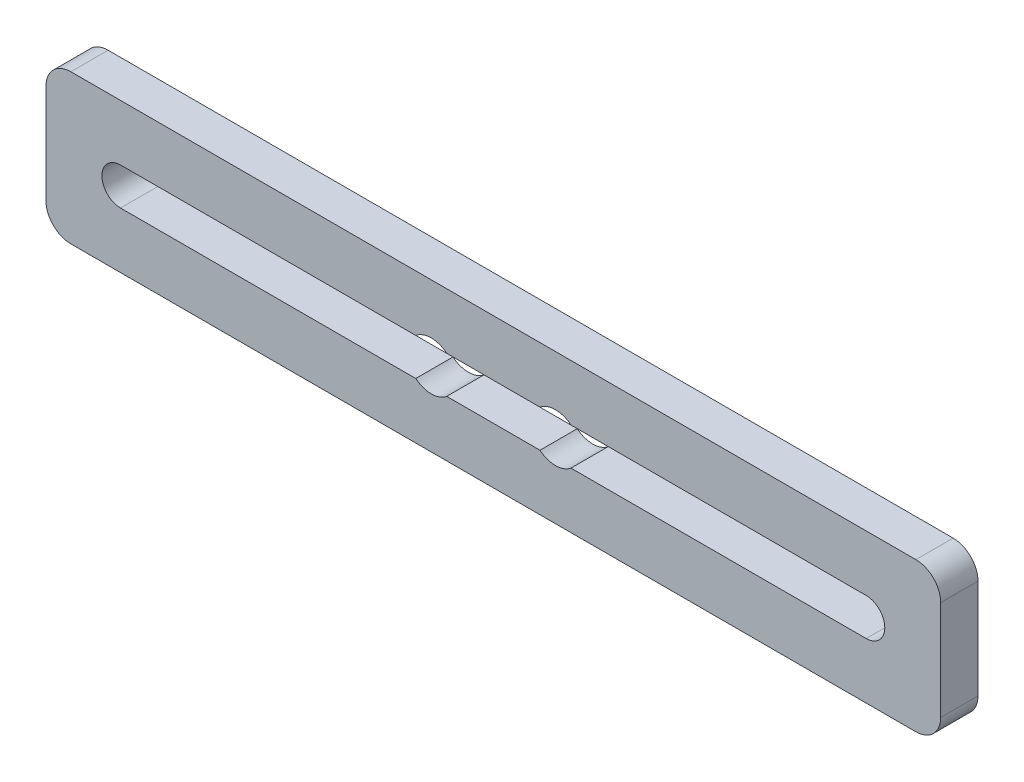
SolidWorks part; units mm, degrees
material "Thornel Mat VMA"
ref_plane "前视基准面" through (0, 0, 0) normal (0, 0, 1) x (1, 0, 0)
ref_plane "上视基准面" through (0, 0, 0) normal (0, 1, 0) x (1, 0, 0)
ref_plane "右视基准面" through (0, 0, 0) normal (1, 0, 0) x (0, 0, -1)
other "Configuration Table"
sketch "草图1" plane through (0, 0, 0) normal (0, 0, 1) x (1, 0, 0)
  line L1 (0, 0) -> (72, 0)
  line L2 (0, 0) -> (0, -12)
  line L3 (0, -12) -> (72, -12)
  line L4 (72, 0) -> (72, -12)
  dimension "D1" = 72
  dimension "D2" = 12
extrude "凸台-拉伸1" add sketch "草图1" along normal blind 3
sketch "草图2" plane through (0, 0, 3) normal (0, 0, 1) x (1, 0, 0)
  line L0 (0, -6) -> (72, -6) construction
  line L1 (0, 0) -> (0, -12) construction
  line L2 (72, -12) -> (72, 0) construction
  line L3 (6, -6) -> (66, -6) construction
  line L6 (6, -4.5) -> (66, -4.5)
  line L7 (6, -7.5) -> (66, -7.5)
  arc A2 (6, -4.5) -> (6, -7.5) centre (6, -6) ccw
  arc A3 (66, -7.5) -> (66, -4.5) centre (66, -6) ccw
  point P8 (36, -6)
  dimension "D1" = 6
  dimension "D2" = 3
  dimension "D3" = 6
extrude "切除-拉伸1" cut sketch "草图2" against normal through all
sketch "草图3" plane through (0, 0, 3) normal (0, 0, 1) x (1, 0, 0)
  line L0 (0, -6) -> (72, -6) construction
  line L1 (0, 0) -> (0, -12) construction
  line L2 (72, -12) -> (72, 0) construction
  line L3 (36, 0) -> (36, -12) construction
  line L4 (72, 0) -> (0, 0) construction
  line L5 (0, -12) -> (72, -12) construction
  circle A0 centre (41, -6) radius 1.95
  circle A1 centre (31, -6) radius 1.95
  dimension "D1" = 3.9
  dimension "D2" = 5
extrude "切除-拉伸2" cut sketch "草图3" against normal through all
fillet "圆角1" radius 2 4 edges at (72, 0, 1.5) (72, -12, 1.5) (0, -12, 1.5) (0, 0, 1.5)
